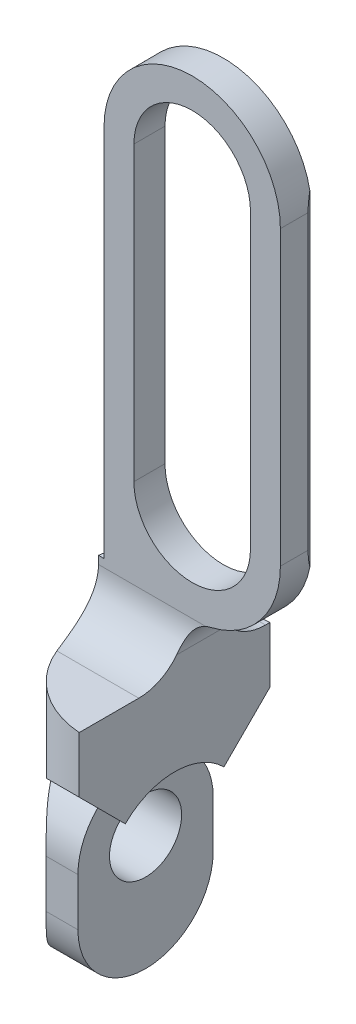
SolidWorks part; units mm, degrees
ref_plane "Front Plane" through (0, 0, 0) normal (0, 0, 1) x (1, 0, 0)
ref_plane "Top Plane" through (0, 0, 0) normal (0, 1, 0) x (1, 0, 0)
ref_plane "Right Plane" through (0, 0, 0) normal (1, 0, 0) x (0, 0, -1)
sketch "Sketch1" plane through (0, 0, 0) normal (0, 1, 0) x (1, 0, 0)
  circle A0 centre (0, 0) radius 4
  dimension "D1" = 4
extrude "Boss-Extrude1" add sketch "Sketch1" along normal blind 38.1 from offset 8 offset against normal yes
sketch "Sketch2" plane through (0, 0, 0) normal (0, 0, 1) x (1, 0, 0)
  line L0 (-0.2833, -8) -> (-0.2833, 7.1091)
  line L1 (-4, -8) -> (4, -8) construction
  line L2 (3.6401, 12.0752) -> (3.6401, 24.3039)
  line L3 (-3.7372, 24.3039) -> (-3.7372, 8.6667)
  line L4 (-3.7372, 8.6667) -> (-4, 8.6667)
  line L5 (-4, 30.1) -> (-4, -8) construction
  line L6 (-4, 8.6667) -> (-4, -8)
  line L7 (-4, -8) -> (-0.2833, -8)
  line L8 (2.3894, 24.3039) -> (2.3894, 12.0752)
  line L9 (-2.4864, 12.0752) -> (-2.4864, 24.3039)
  arc A0 (-0.2833, 7.1091) -> (0.7415, 8.4063) centre (1.05, 7.1091) cw
  arc A1 (0.7415, 8.4063) -> (3.6401, 12.0752) centre (-0.1311, 12.0752) ccw
  arc A2 (3.6401, 24.3039) -> (-3.7372, 24.3039) centre (-0.0485, 24.3039) ccw
  arc A3 (2.3894, 12.0752) -> (-2.4864, 12.0752) centre (-0.0485, 12.0752) cw
  arc A4 (-2.4864, 24.3039) -> (2.3894, 24.3039) centre (-0.0485, 24.3039) cw
  dimension "D1" = 0.2833
  dimension "D3" = 1.3333
  dimension "D4" = 3.7712
  dimension "D9" = 2.4379
  dimension "D2" = 7.1091
  dimension "D5" = 3.9235
  dimension "D6" = 7.3773
  dimension "D7" = 12.2288
  dimension "D8" = 1.5575
extrude "Cut-Extrude1" cut sketch "Sketch2" against normal mid plane 10 flip side to cut
sketch "Sketch3" plane through (3.6401, 0, 0) normal (1, 0, 0) x (0, 0, -1)
  line L0 (-1.5, 6.3333) -> (-6.5, 6.3333)
  line L1 (0.5, 8.3333) -> (0.5, 36.3333)
  line L3 (0.5, 36.3333) -> (-6.5, 36.3333)
  line L4 (-6.5, 36.3333) -> (-6.5, 6.3333)
  line L6 (1.8, 36.3333) -> (1.8, 8.3333)
  line L7 (3.8, 6.3333) -> (5.8, 6.3333)
  line L8 (5.8, 6.3333) -> (5.8, 36.3333)
  line L9 (5.8, 36.3333) -> (1.8, 36.3333)
  arc A0 (-1.5, 6.3333) -> (0.5, 8.3333) centre (-1.5, 8.3333) ccw
  arc A1 (1.8, 8.3333) -> (3.8, 6.3333) centre (3.8, 8.3333) ccw
  dimension "D1" = 2
  dimension "D4" = 1.3
  dimension "D2" = 1.5
  dimension "D3" = 8.3333
  dimension "D5" = 2
  dimension "D6" = 5
  dimension "D7" = 30
extrude "Cut-Extrude2" cut sketch "Sketch3" against normal through all
sketch "Sketch4" plane through (-0.2833, 0, 0) normal (1, 0, 0) x (0, 0, -1)
  line L0 (-2.8284, 0) -> (-2.8284, -2)
  line L1 (2.8284, 0) -> (2.8284, -2)
  line L2 (2, 2) -> (3.99, 3.99)
  line L3 (3.99, -8) -> (3.99, 6.3333) construction
  line L4 (-2, 2) -> (-3.99, 3.99)
  line L5 (-3.99, 6.3333) -> (-3.99, -8) construction
  line L6 (-2, 2) -> (2, 2) construction
  line L7 (0, 0) -> (0, -2) construction
  line L8 (3.99, 3.99) -> (5, 3.99)
  line L9 (-3.99, 3.99) -> (-5, 3.99)
  line L10 (-5, 3.99) -> (-5, -11.01)
  line L11 (-5, -11.01) -> (5, -11.01)
  line L12 (5, -11.01) -> (5, 3.99)
  circle A0 centre (0, 0) radius 1.5083
  arc A1 (2.8284, 0) -> (2, 2) centre (0, 0) ccw
  arc A2 (-2.8284, 0) -> (-2, 2) centre (0, 0) cw
  arc A3 (-2.8284, -2) -> (2.8284, -2) centre (0, -2) ccw
  dimension "D1" = 4
  dimension "D2" = 2
  dimension "D3" = 3.0167
  dimension "D4" = 10
  dimension "D5" = 15
extrude "Cut-Extrude3" cut sketch "Sketch4" against normal through all
sketch "Sketch5" plane through (-0.2833, 0, 0) normal (1, 0, 0) x (0, 0, -1)
  line L0 (-2.9167, 0) -> (-2.9167, -2.54)
  line L1 (2.9167, 0) -> (2.9167, -2.54)
  arc A0 (2.9167, 0) -> (-2.9167, 0) centre (0, 0) ccw
  arc A1 (2.9167, -2.54) -> (-2.9167, -2.54) centre (0, -2.54) cw
  dimension "D1" = 2.9167
  dimension "D2" = 2.54
extrude "Cut-Extrude4" cut sketch "Sketch5" against normal blind 1.2167
